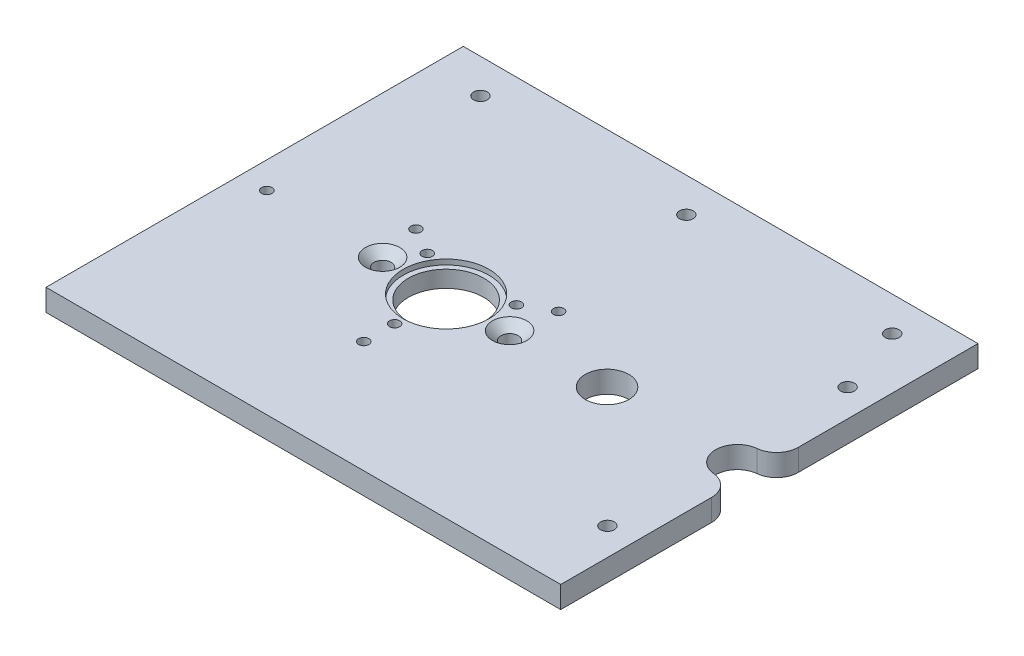
SolidWorks part; units mm, degrees
ref_plane "Alzado" through (0, 0, 0) normal (0, 0, 1) x (1, 0, 0)
ref_plane "Planta" through (0, 0, 0) normal (0, 1, 0) x (1, 0, 0)
ref_plane "Vista lateral" through (0, 0, 0) normal (1, 0, 0) x (0, 0, -1)
sketch "Croquis1" plane through (0, 0, 0) normal (0, 1, 0) x (1, 0, 0)
  line L1 (-75, 50.8) -> (75, 50.8)
  line L2 (-75, 50.8) -> (-75, -50.8)
  line L3 (-75, -50.8) -> (75, -50.8)
  line L4 (75, 50.8) -> (75, -50.8)
  line L5 (-75, 50.8) -> (75, -50.8) construction
  line L6 (-75, -50.8) -> (75, 50.8) construction
  point P0 (0, 0)
  dimension "D1" = 101.6
  dimension "D2" = 150
extrude "Saliente-Extruir1" add sketch "Croquis1" along normal mid plane 6.35
sketch "Croquis2" plane through (0, 3.175, 0) normal (0, 1, 0) x (1, 0, 0)
  line L0 (67, 50.8) -> (67, -50.8) construction
  line L1 (75, 50.8) -> (-75, 50.8) construction
  line L2 (-75, -50.8) -> (75, -50.8) construction
  line L3 (-75, 5.8) -> (75, 5.8) construction
  line L4 (-75, 50.8) -> (-75, -50.8) construction
  line L5 (75, -50.8) -> (75, 50.8) construction
  circle A0 centre (67, 40.8) radius 2
  circle A1 centre (67, -29.2) radius 2
  circle A2 centre (-15, 5.8) radius 11
  circle A3 centre (-67.25, 5.8) radius 1.5
  circle A4 centre (31.9, 5.8) radius 6.35
  circle A5 centre (69.9, 5.8) radius 6.35
  dimension "D3" = 4
  dimension "D6" = 22
  dimension "D7" = 3
  dimension "D9" = 12.7
  dimension "D2" = 8
  dimension "D4" = 35
  dimension "D5" = 82
  dimension "D8" = 52.25
  dimension "D10" = 46.9
  dimension "D11" = 84.9
  dimension "D12" = 45
extrude "Cortar-Extruir1" cut sketch "Croquis2" against normal through all
fillet "Redondeo1" radius 6.35 2 edges at (75, 0, -9.5832) (75, 0, -2.0168)
sketch "Croquis3" plane through (0, 3.175, 0) normal (0, 1, 0) x (1, 0, 0)
  line L0 (-15, 5.8) -> (-15, -18.2) construction
  circle A0 centre (-15, -9.2) radius 1.5
  circle A1 centre (-15, -18.2) radius 1.5
  circle A2 centre (-15, 5.8) radius 20 construction
  circle A3 centre (-15, -18.2) radius 4 construction
  circle A4 centre (-27.9904, 13.3) radius 1.5
  circle A5 centre (-35.7846, 17.8) radius 1.5
  circle A6 centre (-2.0096, 13.3) radius 1.5
  circle A7 centre (5.7846, 17.8) radius 1.5
  point P19 (-15, 5.8)
  dimension "D1" = 3
  dimension "D2" = 3
  dimension "D5" = 40
  dimension "D6" = 8
  dimension "D3" = 15
  dimension "D4" = 24
  dimension "D7" = 3
extrude "Cortar-Extruir2" cut sketch "Croquis3" against normal through all
sketch "Croquis4" plane through (0, 0, 0) normal (0, 1, 0) x (1, 0, 0)
  circle A0 centre (-15, 5.8) radius 12.5
  dimension "D1" = 25
extrude "Cortar-Extruir3" cut sketch "Croquis4" against normal blind 1.5 from surface at 3.175 starting at face at (5.7846, 3.175, -16.3)
sketch "Croquis9" plane through (0, 3.175, 0) normal (0, 1, 0) x (1, 0, 0)
  line L0 (-15, 16.8) -> (-15, 5.8) construction
  line L1 (-15, 5.8) -> (3.5, 5.8) construction
  circle A0 centre (-15, 5.8) radius 11 construction
  circle A1 centre (3.5, 5.8) radius 2.5
  circle A2 centre (-33.5, 5.8) radius 2.5
  dimension "D2" = 5
  dimension "D1" = 18.5
extrude "Cortar-Extruir6" cut sketch "Croquis9" against normal through all
chamfer "Chaflán1" distance 2.5 angle 45 2 edges at (-33.5, 3.175, -8.3) (3.5, 3.175, -3.3)
sketch "Croquis10" plane through (0, 3.175, 0) normal (0, 1, 0) x (1, 0, 0)
  line L0 (75, 50.8) -> (-75, 50.8)
  line L1 (-75, 50.8) -> (-75, 70.8)
  line L2 (-75, 70.8) -> (75, 70.8)
  line L3 (75, 70.8) -> (75, 50.8)
  line L4 (-75, 60.8) -> (75, 60.8) construction
  line L5 (0, 60.8) -> (0, 50.8) construction
  circle A0 centre (0, 60.8) radius 2
  circle A1 centre (-60, 60.8) radius 2
  circle A2 centre (60, 60.8) radius 2
  dimension "D2" = 4
  dimension "D1" = 20
  dimension "D3" = 60
extrude "Saliente-Extruir2" add sketch "Croquis10" against normal up to surface (6.35 mm away) up to face at (3.5, -3.175, -3.3)
